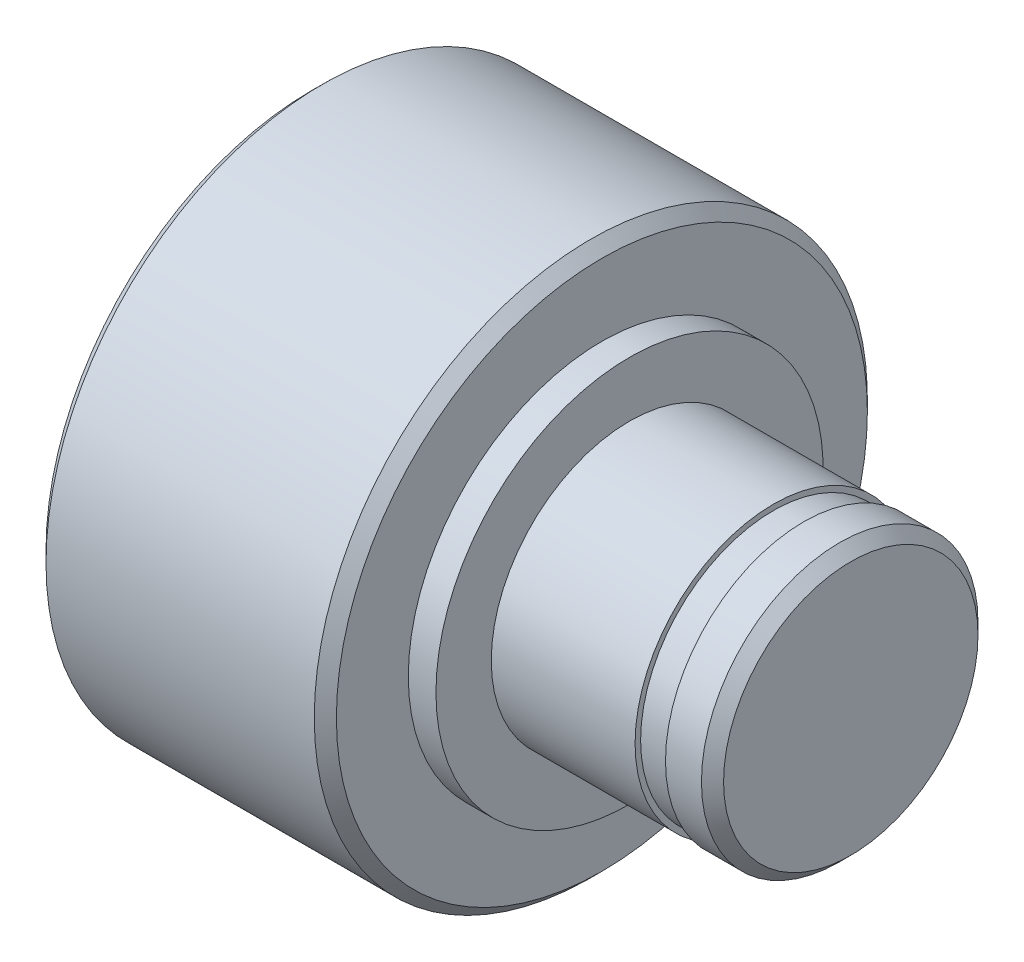
SolidWorks part; units mm, degrees
material "1060 Alloy"
ref_plane "Front Plane" through (0, 0, 0) normal (0, 0, 1) x (1, 0, 0)
ref_plane "Top Plane" through (0, 0, 0) normal (0, 1, 0) x (1, 0, 0)
ref_plane "Right Plane" through (0, 0, 0) normal (1, 0, 0) x (0, 0, -1)
sketch "Sketch1" plane through (0, 0, 0) normal (0, 1, 0) x (1, 0, 0)
  line L0 (0, 0) -> (19.5, 0) construction
  line L1 (0, 0) -> (0, 10)
  line L2 (0, 10) -> (10.5, 10)
  line L3 (10.5, 10) -> (10.5, 7)
  line L4 (11.5, 5) -> (19.5, 5)
  line L5 (19.5, 5) -> (19.5, 0)
  line L6 (10.5, 7) -> (11.5, 7)
  line L7 (11.5, 7) -> (11.5, 5)
  line L8 (0, 0) -> (19.5, 0)
  dimension "D1" = 20
  dimension "D2" = 10
  dimension "D3" = 10.5
  dimension "D4" = 2
  dimension "D5" = 1
  dimension "D6" = 8
revolve "Revolve1" add sketch "Sketch1" angle 360 about L0
chamfer "Chamfer1" distance 0.4 angle 45 3 edges at (10.5, 0, 10) (19.5, 0, 5) (0, 0, 10)
sketch "Sketch2" plane through (0, 0, 0) normal (0, 1, 0) x (1, 0, 0)
  line L0 (16.7, 5) -> (16.7, 4.8)
  line L1 (19.1, 5) -> (11.5, 5) construction
  line L2 (16.7, 4.8) -> (17.8, 4.8)
  line L3 (17.8, 4.8) -> (17.8, 5)
  line L4 (19.1, 5) -> (11.5, 5) construction
  line L5 (17.8, 5) -> (16.7, 5)
  line L6 (11.5, 0) -> (19.1, 0) construction
  line L7 (11.5, -5) -> (11.5, 5) construction
  line L8 (19.1, -5) -> (19.1, 5) construction
  dimension "D1" = 9.6
  dimension "D2" = 1.1
  dimension "D3" = 5.2
revolve "Cut-Revolve1" cut sketch "Sketch2" angle 360 about L6
